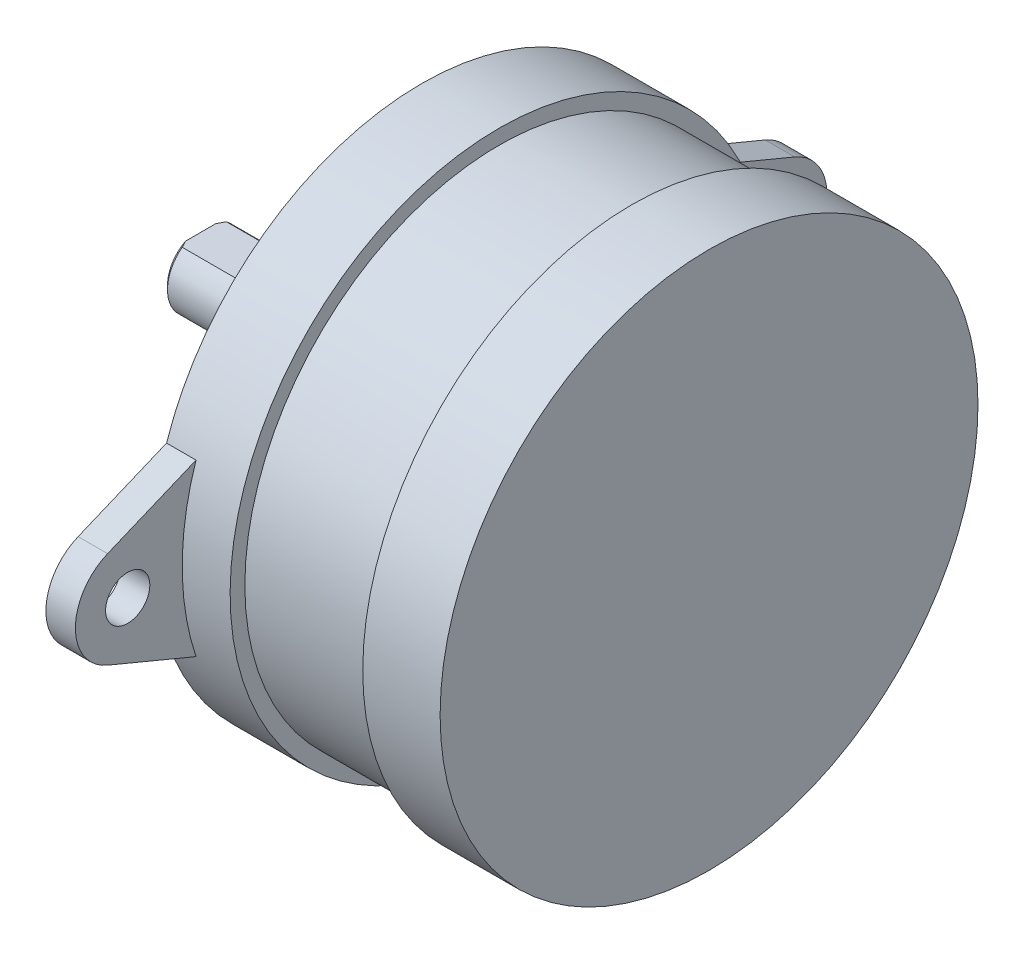
SolidWorks part; units mm, degrees
material "Acier non allié"
ref_plane "Plan de face" through (0, 0, 0) normal (0, 0, 1) x (1, 0, 0)
ref_plane "Plan de dessus" through (0, 0, 0) normal (0, 1, 0) x (1, 0, 0)
ref_plane "Plan de droite" through (0, 0, 0) normal (1, 0, 0) x (0, 0, -1)
sketch "Esquisse2" plane through (0, 0, 0) normal (1, 0, 0) x (0, 0, -1)
  circle A0 centre (0, 0) radius 18.25
  dimension "D1" = 36.5
extrude "Boss.-Extru.1" add sketch "Esquisse2" along normal blind 5.25
sketch "Esquisse3" plane through (5.25, 0, 0) normal (1, 0, 0) x (0, 0, -1)
  circle A0 centre (0, 0) radius 17.25
  dimension "D1" = 34.5
extrude "Boss.-Extru.2" add sketch "Esquisse3" along normal blind 9
sketch "Esquisse4" plane through (14.25, 0, 0) normal (1, 0, 0) x (0, 0, -1)
  circle A0 centre (0, 0) radius 18.25
  dimension "D1" = 36.5
extrude "Boss.-Extru.3" add sketch "Esquisse4" along normal blind 5.25
sketch "Esquisse6" plane through (0, 0, 0) normal (-1, 0, 0) x (0, 0, 1)
  line L0 (0, 0) -> (21.95, 0) construction
  line L1 (0, 0) -> (0, 18.25) construction
  line L2 (21.95, 0) -> (23.3137, 3.2776) construction
  line L3 (21.95, 0) -> (25.5, 0) construction
  line L4 (23.3137, 3.2776) -> (17.3124, 5.7745)
  line L5 (23.3137, -3.2776) -> (17.3124, -5.7745)
  line L6 (-23.3137, 3.2776) -> (-17.3124, 5.7745)
  line L7 (-23.3137, -3.2776) -> (-17.3124, -5.7745)
  circle A0 centre (0, 0) radius 18.25 construction
  circle A1 centre (21.95, 0) radius 1.5
  arc A2 (23.3137, 3.2776) -> (23.3137, -3.2776) centre (21.95, 0) cw
  arc A3 (17.3124, 5.7745) -> (17.294, -5.8292) centre (0, 0) cw
  circle A4 centre (-21.95, 0) radius 1.5
  arc A5 (-23.3137, 3.2776) -> (-23.3137, -3.2776) centre (-21.95, 0) ccw
  arc A6 (-17.3124, 5.7745) -> (-17.294, -5.8292) centre (0, 0) ccw
  circle M5 centre (0, 0) radius 18.25
  dimension "D3" = 3
  dimension "D1" = 21.95
  dimension "D2" = 25.5
  dimension "D4" = 6.5
extrude "Boss.-Extru.4" add sketch "Esquisse6" against normal blind 2 contours A2 L4 L5 A1 M5 | L6 A5 L7 A4 M5
sketch "Esquisse7" plane through (0, 0, 0) normal (-1, 0, 0) x (0, 0, 1)
  circle A0 centre (0, 0) radius 8
  dimension "D1" = 16
extrude "Boss.-Extru.5" add sketch "Esquisse7" along normal blind 2
sketch "Esquisse8" plane through (0, 0, 0) normal (-1, 0, 0) x (0, 0, 1)
  circle A0 centre (0, 0) radius 2.5
  dimension "D1" = 5
extrude "Boss.-Extru.6" add sketch "Esquisse8" along normal blind 15
chamfer "Chanfrein1" distance 0.25 angle 45 1 edges at (-15, 0, 2.5)
sketch "Esquisse9" plane through (-15, 0, 0) normal (-1, 0, 0) x (0, 0, 1)
  line L1 (-2.5, 2) -> (2.5, 2)
  line L2 (-2.5, 2) -> (-2.5, 3)
  line L3 (-2.5, 3) -> (2.5, 3)
  line L4 (2.5, 2) -> (2.5, 3)
  dimension "D1" = 5
  dimension "D2" = 2.5
  dimension "D3" = 2
  dimension "D4" = 1
extrude "Enlèv. mat.-Extru.1" cut sketch "Esquisse9" against normal blind 10
